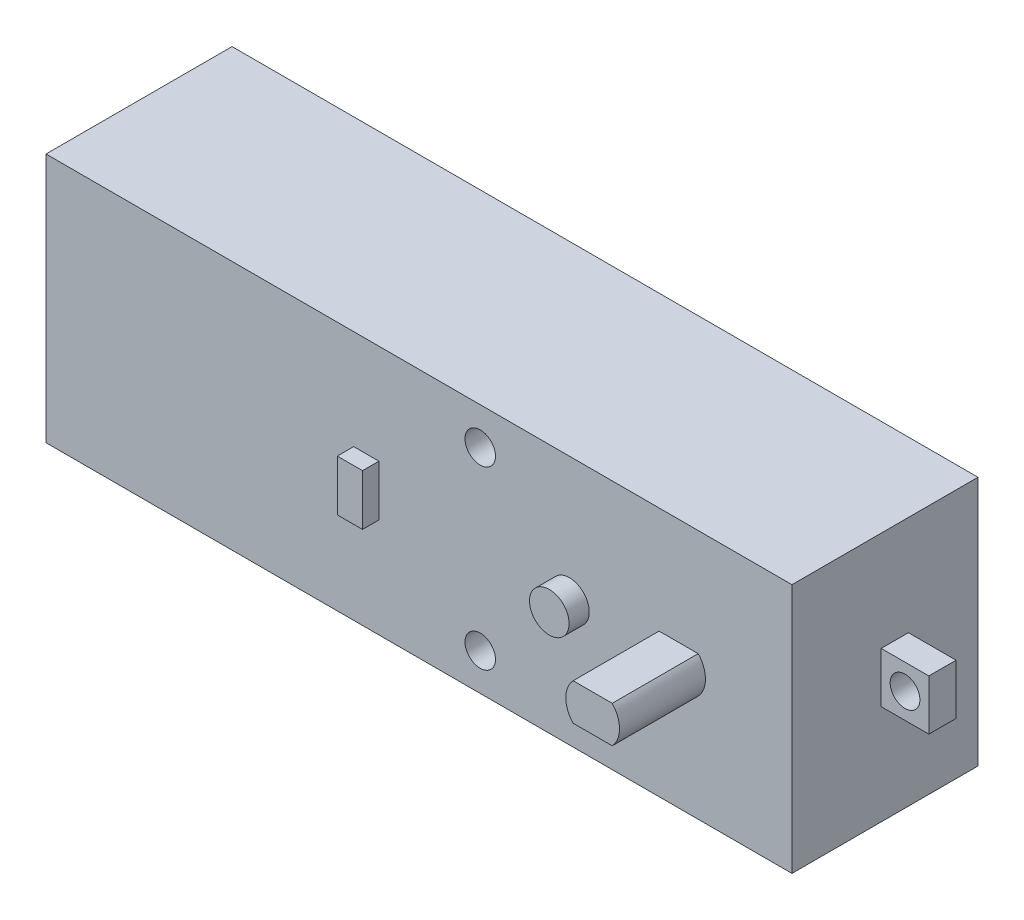
SolidWorks part; units mm, degrees
material "Copper"
ref_plane "Front Plane" through (0, 0, 0) normal (0, 0, 1) x (1, 0, 0)
ref_plane "Top Plane" through (0, 0, 0) normal (0, 1, 0) x (1, 0, 0)
ref_plane "Right Plane" through (0, 0, 0) normal (1, 0, 0) x (0, 0, -1)
sketch "Sketch1" plane through (0, 0, 0) normal (0, 0, 1) x (1, 0, 0)
  line L1 (0, 0) -> (75.1586, 0)
  line L2 (0, 0) -> (0, 25.1968)
  line L3 (0, 25.1968) -> (75.1586, 25.1968)
  line L4 (75.1586, 0) -> (75.1586, 25.1968)
  dimension "D1" = 75.1586
  dimension "D2" = 25.1968
extrude "Boss-Extrude1" add sketch "Sketch1" along normal blind 18.7452
ref_plane "Plane1" through (0, 0, 7.0104) normal (0, 0, 1) x (1, 0, 0)
sketch "Sketch2" plane through (0, 0, 7.0104) normal (0, 0, 1) x (1, 0, 0)
  line L0 (75.1586, 0) -> (75.1586, 25.1968) construction
  line L1 (75.1586, 10.0584) -> (79.9592, 10.0584)
  line L2 (75.1586, 10.0584) -> (75.1586, 15.1384)
  line L3 (75.1586, 15.1384) -> (79.9592, 15.1384)
  line L4 (79.9592, 10.0584) -> (79.9592, 15.1384)
  point P6 (75.1586, 12.5984)
  point P7 (75.1586, 12.5984)
  dimension "D1" = 5.08
  dimension "D2" = 4.8006
extrude "Boss-Extrude2" add sketch "Sketch2" along normal blind 2.7432
sketch "Sketch4" plane through (0, 0, 9.7536) normal (0, 0, 1) x (1, 0, 0)
  line L0 (75.1586, 15.1384) -> (79.9592, 10.0584) construction
  circle A0 centre (77.5589, 12.5984) radius 1.4986
  dimension "D1" = 2.9972
extrude "Cut-Extrude1" cut sketch "Sketch4" against normal through all
sketch "Sketch3" plane through (0, 0, 18.7452) normal (0, 0, 1) x (1, 0, 0)
  line L0 (0, 25.1968) -> (0, 0) construction
  circle A0 centre (52.7431, 12.5984) radius 1.9939
  circle A1 centre (77.5589, 12.5984) radius 1.4986 construction
  point P4 (0, 12.5984)
  dimension "D1" = 3.9878
  dimension "D2" = 24.8158
extrude "Boss-Extrude3" add sketch "Sketch3" along normal blind 2.032
sketch "Sketch5" plane through (0, 0, 18.7452) normal (0, 0, 1) x (1, 0, 0)
  line L0 (0, 25.1968) -> (0, 0) construction
  circle A0 centre (63.7413, 12.5984) radius 2.7051
  circle A2 centre (52.7431, 12.5984) radius 1.9939 construction
  point P7 (0, 12.5984)
  dimension "D1" = 5.4102
  dimension "D2" = 10.9982
extrude "Boss-Extrude4" add sketch "Sketch5" along normal blind 8.6614
sketch "Sketch6" plane through (0, 0, 27.4066) normal (0, 0, 1) x (1, 0, 0)
  line L0 (61.7717, 10.7442) -> (65.7109, 10.7442)
  line L1 (61.7717, 14.4526) -> (65.7109, 14.4526)
  circle A0 centre (63.7413, 12.5984) radius 2.7051 construction
  circle A1 centre (63.7413, 12.5984) radius 2.7051
  circle M3 centre (63.7413, 12.5984) radius 2.7051
  dimension "D1" = 3.7084
extrude "Cut-Extrude2" cut sketch "Sketch6" against normal up to surface (8.6614 mm away) contours L1 M3 | L0 M3 up to face at (61.0362, 12.5984, 18.7452)
sketch "Sketch7" plane through (0, 0, 18.7452) normal (0, 0, 1) x (1, 0, 0)
  line L0 (43.7515, 21.463) -> (43.7515, 3.7338) construction
  line L1 (43.7515, 12.5984) -> (0, 12.5984) construction
  line L2 (0, 25.1968) -> (0, 0) construction
  circle A0 centre (43.7515, 21.463) radius 1.5367
  circle A1 centre (43.7515, 3.7338) radius 1.5367
  circle A2 centre (52.7431, 12.5984) radius 1.9939 construction
  dimension "D1" = 3.0734
  dimension "D2" = 8.9916
  dimension "D3" = 17.7292
extrude "Cut-Extrude3" cut sketch "Sketch7" against normal through all
sketch "Sketch8" plane through (0, 0, 18.7452) normal (0, 0, 1) x (1, 0, 0)
  line L0 (33.5407, 12.5984) -> (52.7431, 12.5984) construction
  line L1 (31.0007, 15.1638) -> (33.5407, 15.1638)
  line L2 (31.0007, 15.1638) -> (31.0007, 10.033)
  line L3 (31.0007, 10.033) -> (33.5407, 10.033)
  line L4 (33.5407, 15.1638) -> (33.5407, 10.033)
  dimension "D1" = 5.1308
  dimension "D2" = 2.54
  dimension "D3" = 19.2024
extrude "Boss-Extrude5" add sketch "Sketch8" along normal blind 1.651
ref_plane "Plane2" through (0, 12.5984, 0) normal (0, 1, 0) x (1, 0, 0)
